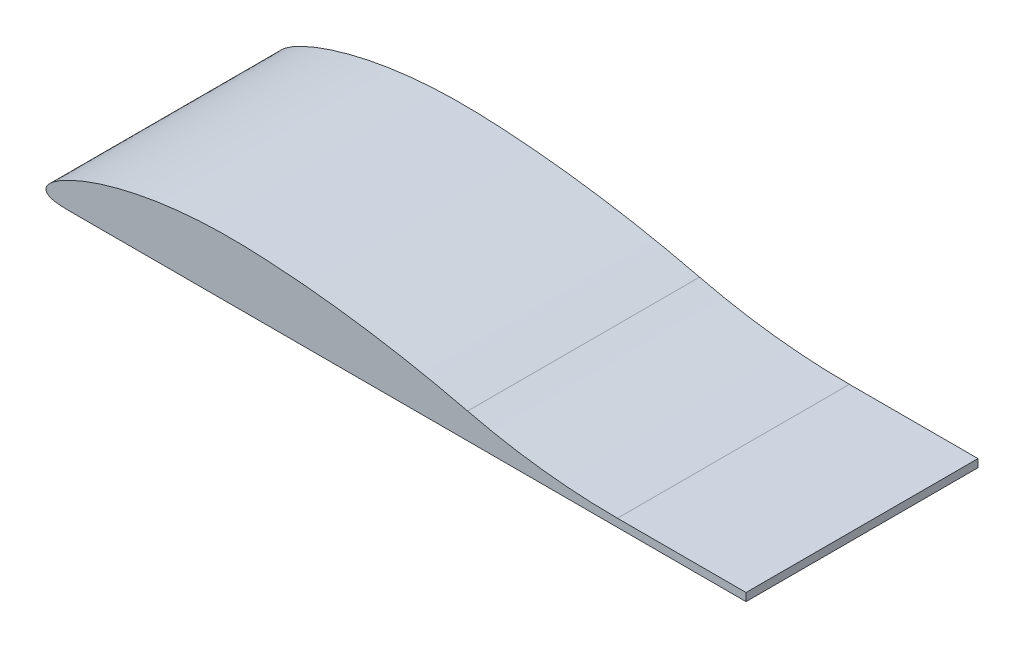
SolidWorks part; units mm, degrees
ref_plane "Front Plane" through (0, 0, 0) normal (0, 0, 1) x (1, 0, 0)
ref_plane "Top Plane" through (0, 0, 0) normal (0, 1, 0) x (1, 0, 0)
ref_plane "Right Plane" through (0, 0, 0) normal (1, 0, 0) x (0, 0, -1)
curve "Curve1"
  spline degree 3 poles (302.9843, 0.2066, 0) (305.2463, -0.0888, 0) (303.0423, 0.5058, 0) (301.2607, 1.1313, 0) (296.8595, 2.4314, 0) (291.4283, 4.0595, 0) (284.2715, 6.1062, 0) (275.7591, 8.441, 0) (265.8676, 11.0139, 0) (254.7283, 13.724, 0) (242.4522, 16.5013, 0) (229.1619, 19.2495, 0) (215.0022, 21.8919, 0) (200.1221, 24.3477, 0) (184.6818, 26.5449, 0) (168.8517, 28.4234, 0) (152.8082, 29.9307, 0) (136.7266, 31.0049, 0) (120.7051, 31.6889, 0) (104.9137, 31.6962, 0) (89.5649, 30.8862, 0) (74.9378, 29.3709, 0) (61.2207, 27.2233, 0) (48.5868, 24.554, 0) (37.1861, 21.5011, 0) (27.1553, 18.1971, 0) (18.5969, 14.8045, 0) (11.6064, 11.436, 0) (6.2054, 8.2632, 0) (2.4621, 5.3102, 0) (0.1728, 2.7181, 0) (-0.3667, -0.1067, 0) (1.6185, -2.1752, 0) (4.9031, -3.1118, 0) (9.5405, -3.659, 0) (15.6223, -3.6847, 0) (23.0877, -3.3095, 0) (31.8617, -2.5607, 0) (41.8437, -1.5362, 0) (52.932, -0.3245, 0) (65.0085, 0.9827, 0) (77.9641, 2.2775, 0) (91.674, 3.4466, 0) (106.0204, 4.4121, 0) (120.9553, 5.0518, 0) (136.3391, 5.4103, 0) (152.0077, 5.7293, 0) (167.7158, 5.8914, 0) (183.2867, 5.9078, 0) (198.553, 5.7595, 0) (213.3478, 5.4574, 0) (227.5084, 5.0134, 0) (240.8771, 4.4585, 0) (253.3023, 3.8196, 0) (264.6365, 3.1406, 0) (274.7593, 2.4517, 0) (283.5118, 1.8033, 0) (290.9024, 1.2074, 0) (296.5367, 0.7424, 0) (301.0977, 0.3102, 0) (302.9843, 0.2066, 0) (305.2463, -0.0888, 0) (303.0423, 0.5058, 0) knots -0.012269 -0.005489 -0.001366 0 0.001375 0.005484 0.012273 0.021682 0.033581 0.047831 0.064306 0.082777 0.103064 0.124929 0.148149 0.172445 0.197572 0.223269 0.249228 0.275186 0.300901 0.326463 0.351222 0.374906 0.39727 0.418072 0.43708 0.454093 0.46892 0.481392 0.491447 0.499024 0.504294 0.507922 0.51154 0.516781 0.524216 0.533992 0.546034 0.56022 0.576403 0.594371 0.613951 0.634917 0.657089 0.68023 0.704175 0.72909 0.754354 0.779668 0.80476 0.829359 0.853209 0.876041 0.897604 0.917662 0.93597 0.95231 0.966503 0.97835 0.987731 0.994511 0.998634 1 1.001375 1.005484 1.012273 periodic
sketch "Sketch1" plane through (0, 0, 0) normal (0, 0, 1) x (1, 0, 0)
  line L0 (397.4027, 0) -> (397.4027, -11.2558) construction
  line L1 (397.4027, -11.2558) -> (0, -11.2558) construction
  line L2 (0, -11.2558) -> (0, 0) construction
  line L3 (397.4027, 0) -> (397.4027, 42.136) construction
  line L4 (397.4027, 42.136) -> (0, 42.136) construction
  line L5 (0, 42.136) -> (0, 0) construction
  line L6 (16.8245, -3.584) -> (558.8, -3.584)
  line L7 (558.8, -3.584) -> (558.8, 2.766)
  line L8 (558.8, 2.766) -> (388.5279, 2.766)
  line L9 (397.4027, 0) -> (0, 0) construction
  spline S1 degree 3 poles (395.0322, 0.2772) (397.9852, -0.1177) (395.1091, 0.6677) (392.7847, 1.492) (387.0417, 3.208) (379.9549, 5.3566) (370.6158, 8.059) (359.5074, 11.1431) (346.5989, 14.5439) (332.0611, 18.1288) (316.0389, 21.8064) (298.6919, 25.4499) (280.2091, 28.9588) (260.7844, 32.227) (240.6272, 35.1598) (219.9595, 37.6778) (199.0115, 39.7119) (178.012, 41.1805) (157.0894, 42.1393) (136.4647, 42.2132) (116.4146, 41.2179) (97.3043, 39.2985) (79.38, 36.5495) (62.8681, 33.1148) (47.9656, 29.1739) (34.851, 24.8995) (23.6593, 20.5034) (14.5153, 16.1325) (7.4482, 12.0105) (2.5471, 8.169) (-0.4534, 4.7928) (-1.1696, 1.1056) (1.4149, -1.6041) (5.701, -2.8408) (11.7555, -3.5745) (19.6988, -3.6327) (29.4507, -3.1732) (40.9133, -2.231) (53.9547, -0.9336) (68.4418, 0.6036) (84.2201, 2.2618) (101.1464, 3.9) (119.0574, 5.371) (137.7989, 6.5735) (157.3077, 7.348) (177.4016, 7.7535) (197.8673, 8.1063) (218.3839, 8.2538) (238.7209, 8.2118) (258.6593, 7.9558) (277.9812, 7.5009) (296.4742, 6.8632) (313.9325, 6.084) (330.1583, 5.1987) (344.9588, 4.2658) (358.1772, 3.3246) (369.606, 2.4422) (379.2564, 1.6336) (386.6132, 1.0034) (392.5685, 0.4203) (395.0322, 0.2772) (397.9852, -0.1177) (395.1091, 0.6677) knots -0.012269 -0.005489 -0.001366 0 0.001375 0.005484 0.012273 0.021682 0.033581 0.047831 0.064306 0.082777 0.103064 0.124929 0.148149 0.172445 0.197572 0.223269 0.249228 0.275186 0.300901 0.326463 0.351222 0.374906 0.39727 0.418072 0.43708 0.454093 0.46892 0.481392 0.491447 0.499024 0.504294 0.507922 0.51154 0.516781 0.524216 0.533992 0.546034 0.56022 0.576403 0.594371 0.613951 0.634917 0.657089 0.68023 0.704175 0.72909 0.754354 0.779668 0.80476 0.829359 0.853209 0.876041 0.897604 0.917662 0.93597 0.95231 0.966503 0.97835 0.987731 0.994511 0.998634 1 1.001375 1.005484 1.012273 only from (397.4027, 0) to (397.4027, 0)
  point P9 (407.203, 2.766)
  point P12 (0, 0)
  dimension "D1" = 45.72
  dimension "D2" = 558.8
  dimension "D3" = 6.35
  dimension "D4" = 397.4027
extrude "Boss-Extrude1" add sketch "Sketch1" along normal blind 185.42 contours S1 L6 L7 L8 | S1
fillet "Fillet1" radius 508 1 edges at (388.5279, 2.766, 92.71)
